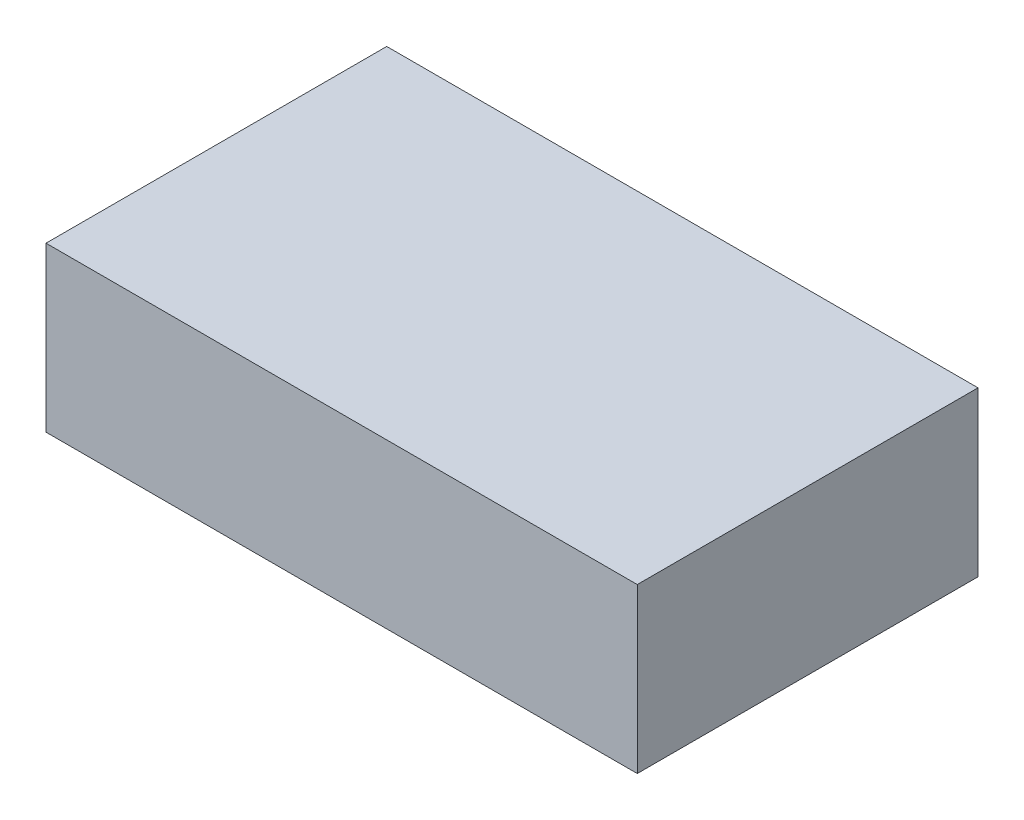
SolidWorks part; units mm, degrees
ref_plane "Front Plane" through (0, 0, 0) normal (0, 0, 1) x (1, 0, 0)
ref_plane "Top Plane" through (0, 0, 0) normal (0, 1, 0) x (1, 0, 0)
ref_plane "Right Plane" through (0, 0, 0) normal (1, 0, 0) x (0, 0, -1)
sketch "Sketch1" plane through (0, 0, 0) normal (0, 1, 0) x (1, 0, 0)
  line L1 (-88.5, -51) -> (88.5, -51)
  line L2 (-88.5, -51) -> (-88.5, 51)
  line L3 (-88.5, 51) -> (88.5, 51)
  line L4 (88.5, -51) -> (88.5, 51)
  line L5 (-88.5, -51) -> (88.5, 51) construction
  line L6 (-88.5, 51) -> (88.5, -51) construction
  point P0 (0, 0)
  dimension "D1" = 177
  dimension "D2" = 102
extrude "Boss-Extrude1" add sketch "Sketch1" along normal blind 49
